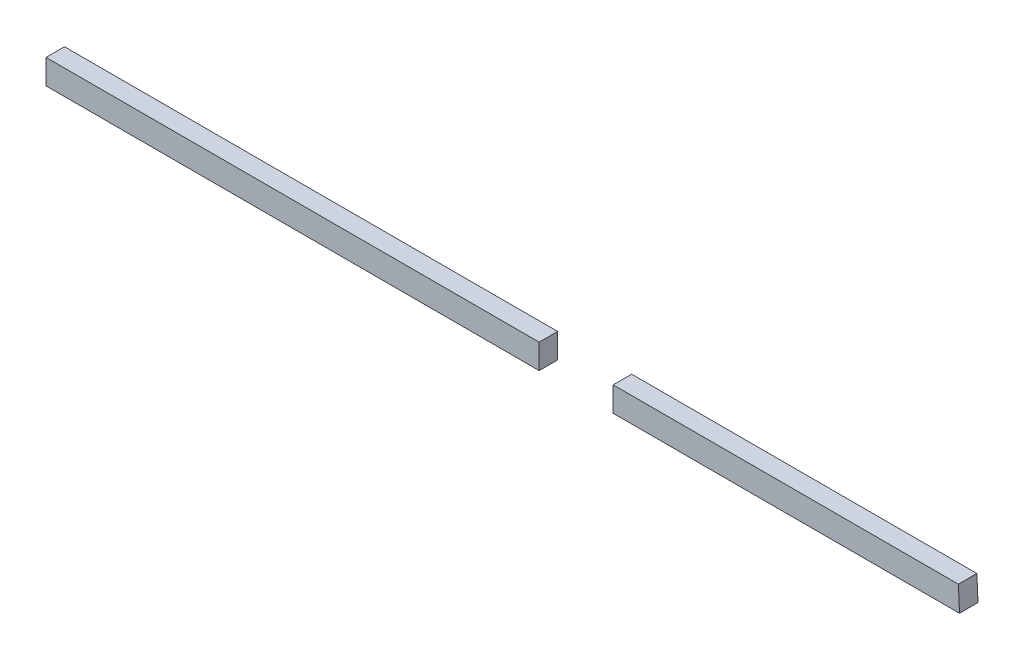
SolidWorks part; units mm, degrees
ref_plane "Front Plane" through (0, 0, 0) normal (0, 0, 1) x (1, 0, 0)
ref_plane "Top Plane" through (0, 0, 0) normal (0, 1, 0) x (1, 0, 0)
ref_plane "Right Plane" through (0, 0, 0) normal (1, 0, 0) x (0, 0, -1)
sketch "Sketch1" plane through (0, 0, 0) normal (0, 0, 1) x (1, 0, 0)
  line L8 (-77.5446, 8.2045) -> (-77.5446, 10.2045)
  line L9 (-77.5446, 10.2045) -> (-37.5446, 10.2045)
  line L10 (-37.5446, 10.2045) -> (-37.5446, 8.2045)
  line L11 (-37.5446, 8.2045) -> (-77.5446, 8.2045)
  line L12 (-31.5446, 10.2045) -> (-31.5446, 8.2045)
  line L13 (-31.5446, 8.2045) -> (-3.4548, 8.2045)
  line L14 (-3.4548, 8.2045) -> (-3.5446, 10.2045)
  line L15 (-3.5446, 10.2045) -> (-31.5446, 10.2045)
extrude "Boss-Extrude1" add sketch "Sketch1" against normal blind 1.5
